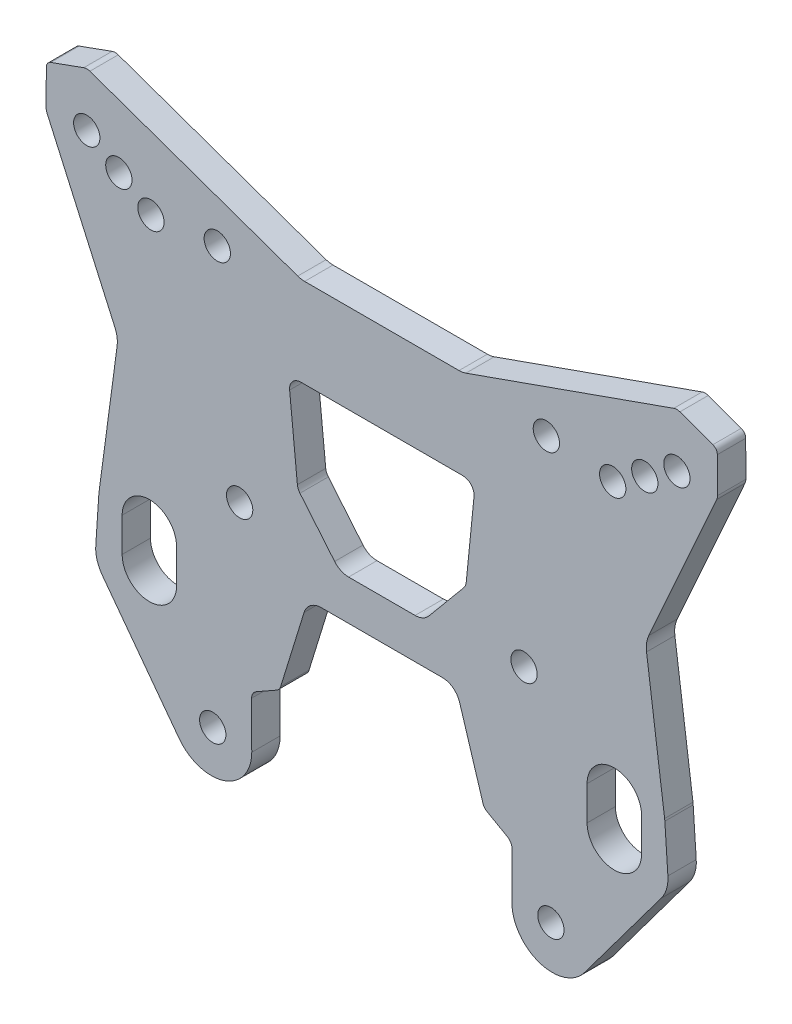
SolidWorks part; units mm, degrees
ref_plane "Front Plane" through (0, 0, 0) normal (0, 0, 1) x (1, 0, 0)
ref_plane "Top Plane" through (0, 0, 0) normal (0, 1, 0) x (1, 0, 0)
ref_plane "Right Plane" through (0, 0, 0) normal (1, 0, 0) x (0, 0, -1)
sketch "Sketch1" plane through (0, 0, 0) normal (0, 0, 1) x (1, 0, 0)
  line L0 (0, 45.5186) -> (0, -52.3294) construction
  line L1 (-8.645, 0) -> (8.645, 0)
  line L2 (9.4171, 0.1325) -> (32.695, 8.3625)
  line L3 (33.3794, 8.36) -> (37.0748, 7.0229)
  line L4 (37.5776, 6.309) -> (37.5912, 2.3362)
  line L5 (37.5026, 1.9175) -> (29.8962, -15.0722)
  line L6 (32.0374, -37.3208) -> (31.6951, -32.1857)
  line L7 (31.6699, -31.9347) -> (29.647, -16.7899)
  line L8 (31.2891, -39.8531) -> (22.7113, -51.3454)
  line L9 (14.5669, -48.6301) -> (14.5796, -43.3894)
  line L10 (14.0642, -42.5028) -> (11.7987, -41.2199)
  line L11 (11.3284, -40.6352) -> (8.7096, -32.1419)
  line L12 (6.7678, -30.7086) -> (-6.7678, -30.7086)
  line L13 (1.4324, -53.1622) -> (35.1159, -53.1622) construction
  line L14 (27.3875, 8.4836) -> (38.3139, 8.4836) construction
  line L15 (-3.7206, -26.2128) -> (3.7206, -26.2128)
  line L16 (5.283, -25.4801) -> (9.1683, -20.8079)
  line L17 (9.4556, -20.1216) -> (10.3259, -11.378)
  line L18 (9.0621, -9.9822) -> (-9.0621, -9.9822)
  line L19 (-27.3875, 8.4836) -> (-38.3139, 8.4836) construction
  line L20 (-1.4324, -53.1622) -> (-35.1159, -53.1622) construction
  line L21 (-9.4556, -20.1216) -> (-10.3259, -11.378)
  line L22 (-5.283, -25.4801) -> (-9.1683, -20.8079)
  line L23 (-11.3284, -40.6352) -> (-8.7096, -32.1419)
  line L24 (-14.0642, -42.5028) -> (-11.7987, -41.2199)
  line L25 (-14.5669, -48.6301) -> (-14.5796, -43.3894)
  line L26 (-31.2891, -39.8531) -> (-22.7113, -51.3454)
  line L27 (-31.6699, -31.9347) -> (-29.647, -16.7899)
  line L28 (-32.0374, -37.3208) -> (-31.6951, -32.1857)
  line L29 (-37.5026, 1.9175) -> (-29.8962, -15.0722)
  line L30 (-37.5776, 6.309) -> (-37.5912, 2.3362)
  line L31 (-33.3794, 8.36) -> (-37.0748, 7.0229)
  line L32 (-9.4171, 0.1325) -> (-32.695, 8.3625)
  arc A0 (22.7113, -51.3454) -> (14.5669, -48.6301) centre (19.0881, -48.641) cw
  arc A1 (8.645, 0) -> (9.4171, 0.1325) centre (8.645, 2.3163) ccw
  arc A2 (33.3794, 8.36) -> (32.695, 8.3625) centre (33.0337, 7.4046) ccw
  arc A3 (37.5776, 6.309) -> (37.0748, 7.0229) centre (36.8156, 6.3064) ccw
  arc A4 (37.5026, 1.9175) -> (37.5912, 2.3362) centre (36.5753, 2.3327) ccw
  arc A5 (29.647, -16.7899) -> (29.8962, -15.0722) centre (32.794, -16.3696) cw
  arc A6 (31.6951, -32.1857) -> (31.6699, -31.9347) centre (27.8935, -32.4391) ccw
  arc A7 (31.2891, -39.8531) -> (32.0374, -37.3208) centre (28.2358, -37.5742) ccw
  arc A8 (14.0642, -42.5028) -> (14.5796, -43.3894) centre (13.5636, -43.3869) cw
  arc A9 (11.3284, -40.6352) -> (11.7987, -41.2199) centre (12.2993, -40.3358) ccw
  arc A10 (8.7096, -32.1419) -> (6.7678, -30.7086) centre (6.7678, -32.7406) ccw
  arc A11 (5.283, -25.4801) -> (3.7206, -26.2128) centre (3.7206, -24.1808) cw
  arc A12 (9.4556, -20.1216) -> (9.1683, -20.8079) centre (8.1919, -19.9959) cw
  arc A13 (9.0621, -9.9822) -> (10.3259, -11.378) centre (9.0621, -11.2522) cw
  arc A14 (-9.0621, -9.9822) -> (-10.3259, -11.378) centre (-9.0621, -11.2522) ccw
  arc A15 (-9.4556, -20.1216) -> (-9.1683, -20.8079) centre (-8.1919, -19.9959) ccw
  arc A16 (-5.283, -25.4801) -> (-3.7206, -26.2128) centre (-3.7206, -24.1808) ccw
  arc A17 (-8.7096, -32.1419) -> (-6.7678, -30.7086) centre (-6.7678, -32.7406) cw
  arc A18 (-11.3284, -40.6352) -> (-11.7987, -41.2199) centre (-12.2993, -40.3358) cw
  arc A19 (-14.0642, -42.5028) -> (-14.5796, -43.3894) centre (-13.5636, -43.3869) ccw
  arc A20 (-31.2891, -39.8531) -> (-32.0374, -37.3208) centre (-28.2358, -37.5742) cw
  arc A21 (-31.6951, -32.1857) -> (-31.6699, -31.9347) centre (-27.8935, -32.4391) cw
  arc A22 (-29.647, -16.7899) -> (-29.8962, -15.0722) centre (-32.794, -16.3696) ccw
  arc A23 (-37.5026, 1.9175) -> (-37.5912, 2.3362) centre (-36.5753, 2.3327) cw
  arc A24 (-37.5776, 6.309) -> (-37.0748, 7.0229) centre (-36.8156, 6.3064) cw
  arc A25 (-33.3794, 8.36) -> (-32.695, 8.3625) centre (-33.0337, 7.4046) cw
  arc A26 (-8.645, 0) -> (-9.4171, 0.1325) centre (-8.645, 2.3163) cw
  arc A27 (-22.7113, -51.3454) -> (-14.5669, -48.6301) centre (-19.0881, -48.641) ccw
  point P3 (-10.4648, -9.9822)
  point P6 (0, -30.7086)
  point P18 (0, 0)
  point P20 (9.0424, 0)
  point P22 (0, -26.2128)
  point P23 (14.581, -42.7954)
  point P26 (33.0376, 8.4836)
  point P28 (33.0376, 8.4836)
  point P29 (37.5757, 6.8417)
  point P32 (37.592, 2.1173)
  point P34 (37.5757, 6.8417)
  point P37 (37.592, 2.1173)
  point P41 (32.131, -38.7252)
  point P42 (29.5275, -15.8956)
  point P44 (11.4474, -41.021)
  point P47 (8.2677, -30.7086)
  point P53 (31.6867, -32.0598)
  point P56 (32.131, -38.7252)
  point P59 (14.581, -42.7954)
  point P62 (11.4474, -41.021)
  point P65 (4.6736, -26.2128)
  point P68 (9.4171, -20.5088)
  point P71 (10.4648, -9.9822)
  point P118 (0, -9.9822)
  point P119 (-9.4171, -20.5088)
  point P120 (-4.6736, -26.2128)
  point P121 (-11.4474, -41.021)
  point P122 (-14.581, -42.7954)
  point P123 (-32.131, -38.7252)
  point P124 (-31.6867, -32.0598)
  point P125 (-8.2677, -30.7086)
  point P126 (-29.5275, -15.8956)
  point P127 (-37.592, 2.1173)
  point P128 (-37.5757, 6.8417)
  point P129 (-33.0376, 8.4836)
  point P130 (-9.0424, 0)
  dimension "D8" = 4.5212
  dimension "D14" = 90.139
  dimension "D15" = 19.7358
  dimension "D16" = 6.6802
  dimension "D17" = 29.5275
  dimension "D18" = 4.6736
  dimension "D19" = 4.4958
  dimension "D20" = 10.4648
  dimension "D11" = 32.131
  dimension "D21" = 16.2306
  dimension "D23" = 2.032
  dimension "D30" = 2.3163
  dimension "D31" = 1.016
  dimension "D32" = 0.762
  dimension "D33" = 1.016
  dimension "D34" = 3.175
  dimension "D35" = 3.81
  dimension "D36" = 3.81
  dimension "D37" = 1.016
  dimension "D38" = 1.016
  dimension "D39" = 2.032
  dimension "D40" = 1.27
  dimension "D41" = 1.27
  dimension "D1" = 9.0424
  dimension "D2" = 25.4508
  dimension "D3" = 4.826
  dimension "D4" = 4.7244
  dimension "D5" = 19.0881
  dimension "D6" = 11.3284
  dimension "D7" = 61.6458
  dimension "D9" = 15.748
  dimension "D10" = 14.5796
  dimension "D12" = 5.461
  dimension "D13" = 8.2677
  dimension "D22" = 30.7086
  dimension "D24" = 8.4836
  dimension "D25" = 10.5786
  dimension "D26" = 7.4187
  dimension "D27" = 10.3124
  dimension "D28" = 16.3077
  dimension "D29" = 37.5757
extrude "Boss-Extrude1" add sketch "Sketch1" along normal blind 3.175
sketch "Sketch2" plane through (0, 0, 3.175) normal (0, 0, 1) x (1, 0, 0)
  line L0 (0, 7.3805) -> (0, -57.3061) construction
  line L1 (34.2862, 3.2458) -> (24.6164, -2.9432) construction
  line L2 (18.4277, -1.4503) -> (16.9291, 2.7884) construction
  line L3 (32.695, 8.3625) -> (9.4171, 0.1325) construction
  line L4 (33.0454, 2.4516) -> (31.1489, 7.8158) construction
  line L5 (-9.4171, 0.1325) -> (-32.695, 8.3625) construction
  line L9 (-18.4277, -1.4503) -> (-16.9291, 2.7884) construction
  line L13 (-34.2862, 3.2458) -> (-24.6164, -2.9432) construction
  line L14 (26.035, -32.893) -> (26.035, -36.703) construction
  line L15 (29.083, -32.893) -> (29.083, -36.703)
  line L16 (22.987, -32.893) -> (22.987, -36.703)
  line L17 (20.2104, -29.845) -> (39.3261, -29.845) construction
  line L18 (44.2385, -39.751) -> (18.6085, -39.751) construction
  line L19 (5.9182, -53.1622) -> (40.322, -53.1622) construction
  line L20 (-11.8919, -30.7086) -> (37.9763, -30.7086) construction
  line L21 (-6.7678, -30.7086) -> (6.7678, -30.7086) construction
  line L22 (-26.035, -32.893) -> (-26.035, -36.703) construction
  line L23 (-29.083, -32.893) -> (-29.083, -36.703)
  line L24 (-22.987, -32.893) -> (-22.987, -36.703)
  circle A0 centre (33.0454, 2.4516) radius 1.4732
  circle A1 centre (29.4513, 0.1513) radius 1.4732
  circle A2 centre (25.8572, -2.149) radius 1.4732
  circle A3 centre (18.4277, -1.4503) radius 1.4732
  circle A4 centre (15.9258, -25.0939) radius 1.4732
  circle A5 centre (18.9357, -48.3953) radius 1.4732
  circle A7 centre (-18.9357, -48.3953) radius 1.4732
  circle A8 centre (-15.9258, -25.0939) radius 1.4732
  circle A9 centre (-18.4277, -1.4503) radius 1.4732
  circle A10 centre (-25.8572, -2.149) radius 1.4732
  circle A11 centre (-29.4513, 0.1513) radius 1.4732
  circle A12 centre (-33.0454, 2.4516) radius 1.4732
  arc A13 (29.083, -32.893) -> (22.987, -32.893) centre (26.035, -32.893) ccw
  arc A14 (22.987, -36.703) -> (29.083, -36.703) centre (26.035, -36.703) ccw
  arc A15 (14.5669, -48.6301) -> (22.7113, -51.3454) centre (19.0881, -48.641) ccw construction
  arc A16 (-29.083, -32.893) -> (-22.987, -32.893) centre (-26.035, -32.893) cw
  arc A17 (-22.987, -36.703) -> (-29.083, -36.703) centre (-26.035, -36.703) cw
  point P44 (26.035, -34.798)
  point P64 (-26.035, -34.798)
  dimension "D1" = 2.9464
  dimension "D3" = 4.2672
  dimension "D12" = 18.9357
  dimension "D13" = 46.7614
  dimension "D14" = 23.495
  dimension "D15" = 15.9258
  dimension "D10" = 36.8554
  dimension "D11" = 51.7144
  dimension "D5" = 66.0908
  dimension "D4" = 4.4958
  dimension "D2" = 4.2672
  dimension "D6" = 90
  dimension "D7" = 5.6896
  dimension "D8" = 90
  dimension "D9" = 90
  dimension "D16" = 6.096
  dimension "D17" = 9.906
  dimension "D18" = 22.987
  dimension "D19" = 0.8636
extrude "Cut-Extrude1" cut sketch "Sketch2" against normal through all
